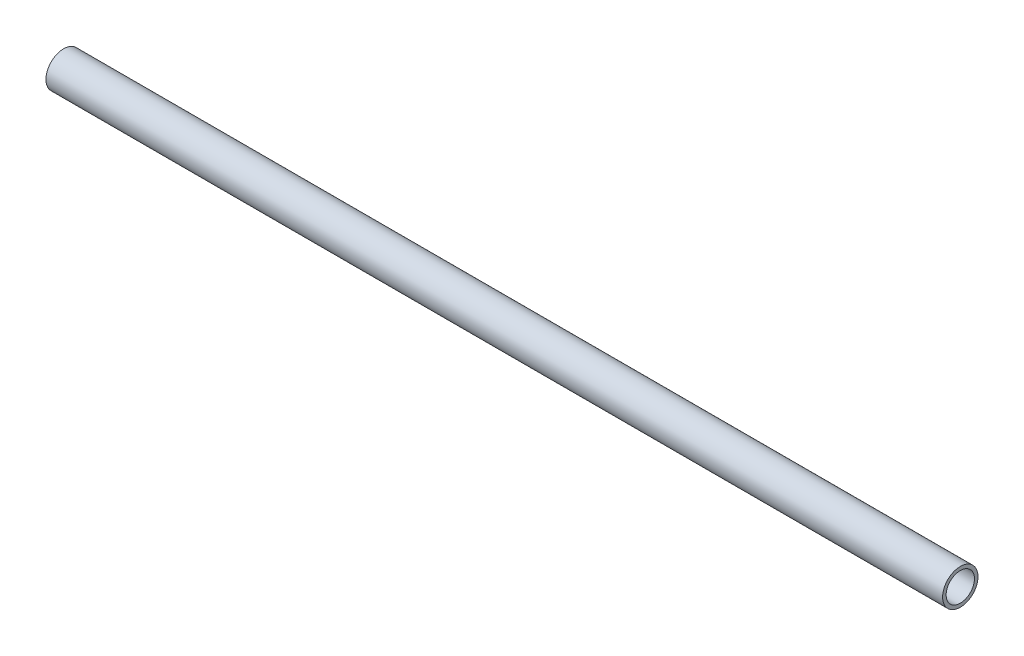
SolidWorks part; units mm, degrees
material "Galvanized Steel"
ref_plane "Front" through (0, 0, 0) normal (0, 0, 1) x (1, 0, 0)
ref_plane "Top" through (0, 0, 0) normal (0, 1, 0) x (1, 0, 0)
ref_plane "Right" through (0, 0, 0) normal (1, 0, 0) x (0, 0, -1)
sketch "Sketch1" plane through (0, 0, 0) normal (1, 0, 0) x (0, 0, -1)
  circle A0 centre (0, 0) radius 9.525
  dimension "D1" = 19.05
extrude "Extrude-Thin1" add sketch "Sketch1" along normal mid plane 482.6 thin thin type one direction reverse wall 1.905
hole_wizard "K (0.281) Diameter Hole1" positions "3DSketch3" profile "Sketch5" hole size "K" standard "Ansi Inch"
sketch3d "3DSketch3"
  point P0 (204.47, 0, -9.525)
  dimension "D1" = 36.83
sketch "Sketch5" plane through (204.47, 0, -9.525) normal (1, 0, 0) x (0, 1, 0)
  line L0 (0, 0) -> (0, 11.6683)
  line L1 (0, 11.6683) -> (3.5687, 9.524)
  line L2 (3.5687, 9.524) -> (3.5687, 0)
  line L5 (3.5687, 0) -> (0, 0)
  line L10 (0, 11.6683) -> (-3.5687, 9.524) construction
  line L11 (0, -6.35) -> (0, 107.95) construction
  dimension "Hole Dia." = 7.1374
  dimension "Hole Depth" = 9.524
  dimension "Drill Angle" = 118
